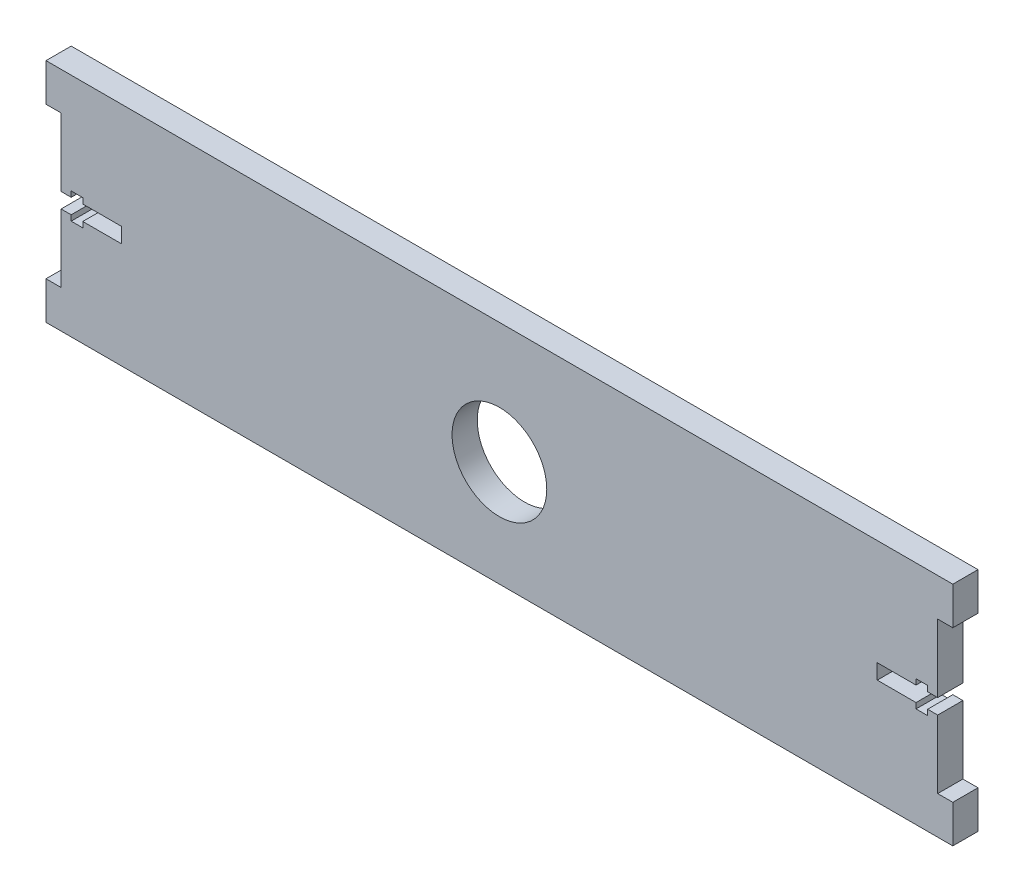
SolidWorks part; units mm, degrees
ref_plane "Plan de face" through (0, 0, 0) normal (0, 0, 1) x (1, 0, 0)
ref_plane "Plan de dessus" through (0, 0, 0) normal (0, 1, 0) x (1, 0, 0)
ref_plane "Plan de droite" through (0, 0, 0) normal (1, 0, 0) x (0, 0, -1)
sketch "Esquisse1" plane through (0, 0, 0) normal (0, 0, 1) x (1, 0, 0)
  line L0 (90, 0) -> (90, 45) construction
  line L1 (90, 45) -> (34.5, 45)
  line L5 (-34.5, 45) -> (-90, 45)
  line L6 (-90, 45) -> (-90, 0) construction
  line L7 (-90, 0) -> (90, 0)
  line L8 (0, 0) -> (0, 89.8) construction
  line L9 (-90, 45) -> (-90, 37.5)
  line L10 (-90, 37.5) -> (-87, 37.5)
  line L11 (-87, 37.5) -> (-87, 24)
  line L12 (-87, 24) -> (-85, 24)
  line L13 (-85, 24) -> (-85, 25.1)
  line L14 (-85, 25.1) -> (-82.7, 25.1)
  line L15 (-82.7, 25.1) -> (-82.7, 24)
  line L16 (-82.7, 24) -> (-75, 24)
  line L17 (-75, 24) -> (-75, 21)
  line L18 (-75, 21) -> (-82.7, 21)
  line L19 (-82.7, 21) -> (-82.7, 19.9)
  line L20 (-82.7, 19.9) -> (-85, 19.9)
  line L21 (-85, 19.9) -> (-85, 21)
  line L22 (-85, 21) -> (-87, 21)
  line L23 (-87, 21) -> (-87, 7.5)
  line L24 (-87, 7.5) -> (-90, 7.5)
  line L25 (-90, 7.5) -> (-90, 0)
  line L26 (-90, 22.5) -> (-42.3783, 22.5) construction
  line L27 (90, 22.5) -> (42.3783, 22.5) construction
  line L28 (90, 45) -> (90, 0) construction
  line L29 (90, 7.5) -> (90, 0)
  line L30 (87, 7.5) -> (90, 7.5)
  line L31 (87, 21) -> (87, 7.5)
  line L32 (85, 21) -> (87, 21)
  line L33 (85, 19.9) -> (85, 21)
  line L34 (82.7, 19.9) -> (85, 19.9)
  line L35 (82.7, 21) -> (82.7, 19.9)
  line L36 (75, 21) -> (82.7, 21)
  line L37 (75, 24) -> (75, 21)
  line L38 (82.7, 24) -> (75, 24)
  line L39 (82.7, 25.1) -> (82.7, 24)
  line L40 (85, 25.1) -> (82.7, 25.1)
  line L41 (85, 24) -> (85, 25.1)
  line L42 (87, 24) -> (85, 24)
  line L43 (87, 37.5) -> (87, 24)
  line L44 (90, 37.5) -> (87, 37.5)
  line L45 (90, 45) -> (90, 37.5)
  line L46 (-17.7718, 33) -> (6.3703, 33) construction
  line L49 (-34.5, 45) -> (34.5, 45)
  circle A0 centre (0, 21) radius 12 construction
  circle A1 centre (0, 21) radius 9.4
  point P4 (33.5469, 45)
  point P5 (-33.6371, 45)
  point P36 (-88.5, 7.5)
  dimension "D12" = 24
  dimension "D15" = 18.8
  dimension "D2" = 180
  dimension "D5" = 30
  dimension "D6" = 3
  dimension "D7" = 15
  dimension "D8" = 2.3
  dimension "D9" = 5.2
  dimension "D10" = 3
  dimension "D11" = 2
  dimension "D14" = 45
  dimension "D18" = 69
  dimension "D19" = 21
  dimension "D20" = 12
extrude "Boss.-Extru.1" add sketch "Esquisse1" along normal blind 5
